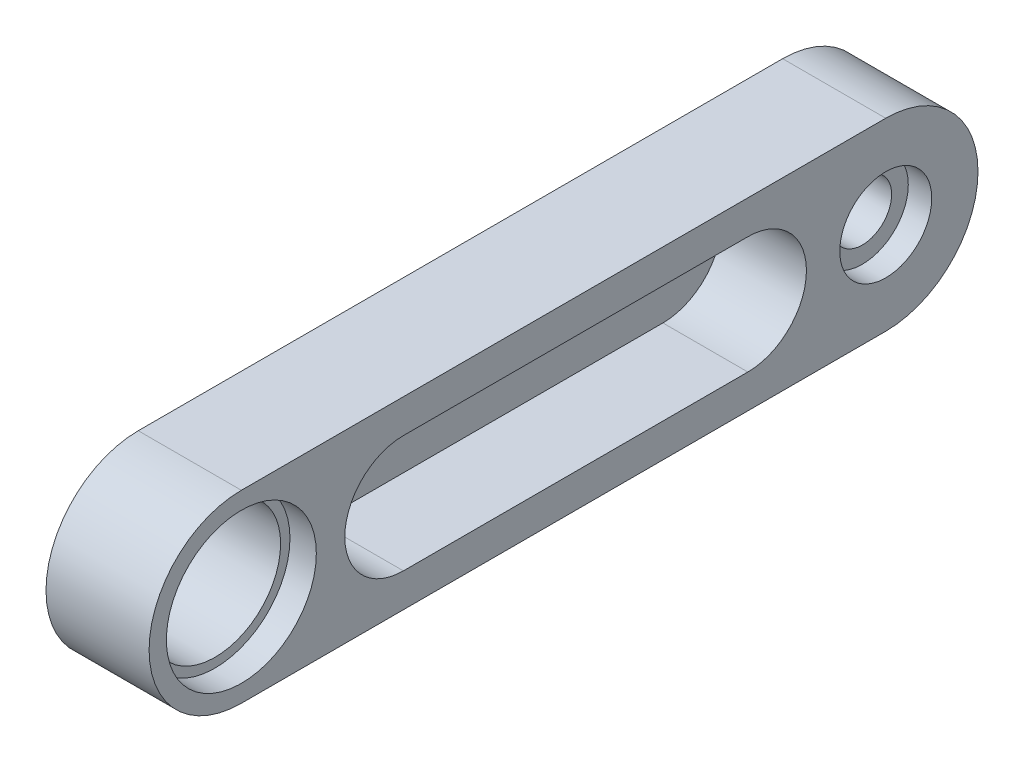
SolidWorks part; units mm, degrees
ref_plane "Front Plane" through (0, 0, 0) normal (0, 0, 1) x (1, 0, 0)
ref_plane "Top Plane" through (0, 0, 0) normal (0, 1, 0) x (1, 0, 0)
ref_plane "Right Plane" through (0, 0, 0) normal (1, 0, 0) x (0, 0, -1)
sketch "Sketch1" plane through (0, 0, 0) normal (1, 0, 0) x (0, 0, -1)
  line L0 (0, 0) -> (27.94, 0) construction
  line L1 (0, 4) -> (27.94, 4)
  line L2 (0, -4) -> (27.94, -4)
  arc A0 (0, 4) -> (0, -4) centre (0, 0) ccw
  arc A1 (27.94, -4) -> (27.94, 4) centre (27.94, 0) ccw
  circle A2 centre (0, 0) radius 2.8448
  circle A3 centre (27.94, 0) radius 1.27
  point P3 (13.97, 0)
  dimension "D1" = 27.94
  dimension "D2" = 4
  dimension "D3" = 5.6896
  dimension "D4" = 2.54
extrude "Boss-Extrude1" add sketch "Sketch1" along normal blind 4.4704
sketch "Sketch2" plane through (4.4704, 0, 0) normal (1, 0, 0) x (0, 0, -1)
  circle A0 centre (0, 0) radius 3.2512
  dimension "D1" = 6.5024
extrude "Cut-Extrude1" cut sketch "Sketch2" against normal blind 1.143
sketch "Sketch3" plane through (4.4704, 0, 0) normal (1, 0, 0) x (0, 0, -1)
  circle A0 centre (27.94, 0) radius 1.9939
  dimension "D1" = 3.9878
extrude "Cut-Extrude2" cut sketch "Sketch3" against normal blind 1.016
sketch "Sketch4" plane through (4.4704, 0, 0) normal (1, 0, 0) x (0, 0, -1)
  line L0 (3.2512, 0) -> (25.9461, 0) construction
  line L1 (7.026, 0) -> (21.9612, 0) construction
  line L2 (7.026, 2.54) -> (21.9612, 2.54)
  line L3 (7.026, -2.54) -> (21.9612, -2.54)
  circle A0 centre (0, 0) radius 3.2512 construction
  arc A1 (7.026, 2.54) -> (7.026, -2.54) centre (7.026, 0) ccw
  circle A2 centre (27.94, 0) radius 1.9939 construction
  arc A3 (21.9612, -2.54) -> (21.9612, 2.54) centre (21.9612, 0) ccw
  point P8 (14.4936, 0)
  dimension "D1" = 2.54
  dimension "D2" = 14.9352
extrude "Cut-Extrude3" cut sketch "Sketch4" against normal blind 3.683
scale "Scale1" scale about centroid uniform scaling yes scale factor 0.6
